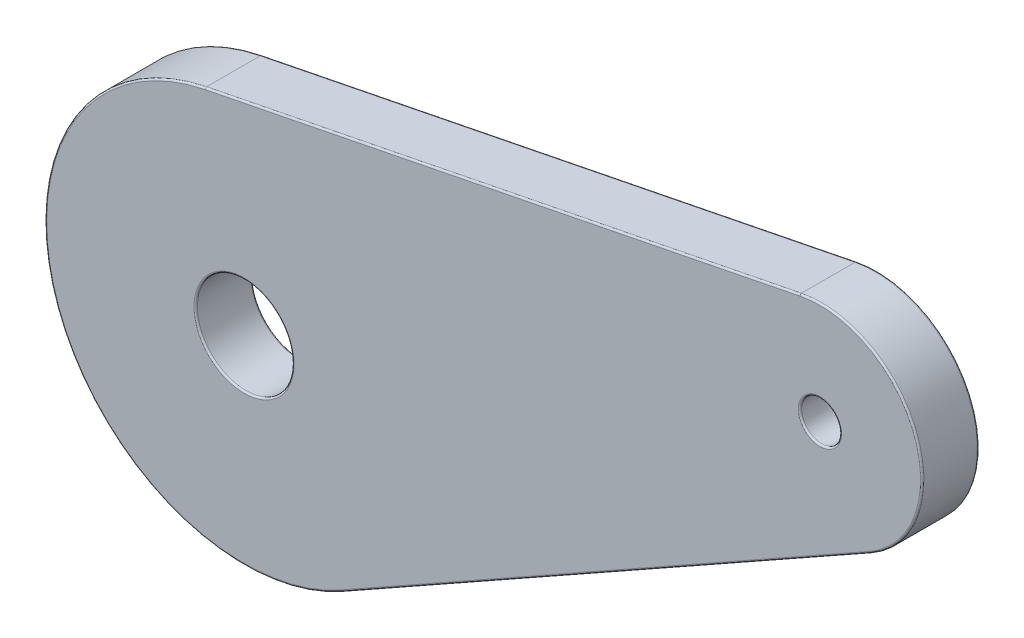
SolidWorks part; units mm, degrees
material "AISI 1020"
ref_plane "Front Plane" through (0, 0, 0) normal (0, 0, 1) x (1, 0, 0)
ref_plane "Top Plane" through (0, 0, 0) normal (0, 1, 0) x (1, 0, 0)
ref_plane "Right Plane" through (0, 0, 0) normal (1, 0, 0) x (0, 0, -1)
sketch "Sketch1" plane through (0, 0, 0) normal (0, 0, 1) x (1, 0, 0)
  line L0 (-20.22, 57.58) -> (30.4151, 76.3439) construction
  line L1 (-20.22, 57.58) -> (30.4151, 76.3439) construction
  line L2 (-23.6421, 74.7421) -> (28.6552, 85.1701)
  line L3 (34.8319, 68.5022) -> (-11.6319, 42.3322)
  circle A0 centre (-20.22, 57.58) radius 17.5 construction
  circle A1 centre (-20.22, 57.58) radius 17.5 construction
  circle A2 centre (30.4151, 76.3439) radius 9 construction
  arc A3 (28.6552, 85.1701) -> (34.8319, 68.5022) centre (30.4151, 76.3439) cw
  arc A4 (-23.6421, 74.7421) -> (-11.6319, 42.3322) centre (-20.22, 57.58) ccw
  circle A5 centre (30.4151, 76.3439) radius 1.75
  circle A6 centre (-20.22, 57.58) radius 4.25
  dimension "D1" = 18
  dimension "D2" = 3.5
  dimension "D3" = 8.5
extrude "Boss-Extrude1" add sketch "Sketch1" along normal blind 5
fillet "Fillet1" radius 0.15 12 edges at (11.6, 55.4172, 5) (38.8543, 79.4712, 5) (2.5066, 79.9561, 5) (-36.6295, 51.4991, 5) (32.1651, 76.3439, 5) (-15.97, 57.58, 5) (2.5066, 79.9561, 0) (38.8543, 79.4712, 0) (11.6, 55.4172, 0) (-36.6295, 51.4991, 0) (32.1651, 76.3439, 0) (-15.97, 57.58, 0)
